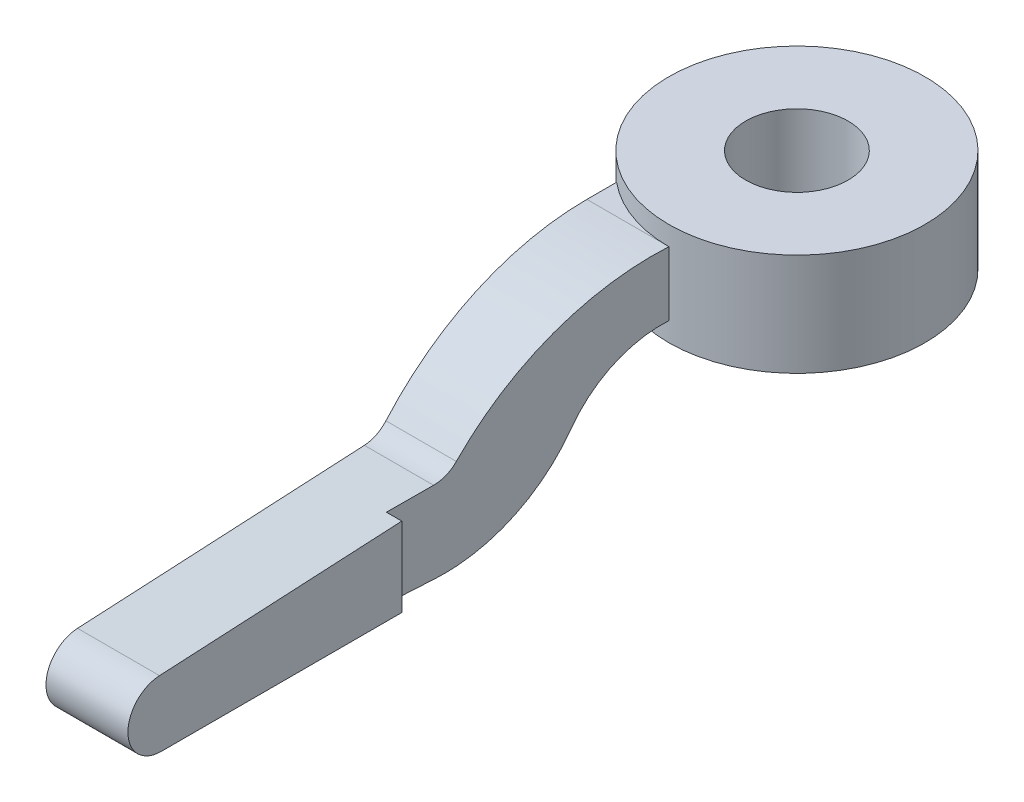
SolidWorks part; units mm, degrees
ref_plane "Front Plane" through (0, 0, 0) normal (0, 0, 1) x (1, 0, 0)
ref_plane "Top Plane" through (0, 0, 0) normal (0, 1, 0) x (1, 0, 0)
ref_plane "Right Plane" through (0, 0, 0) normal (1, 0, 0) x (0, 0, -1)
sketch "Sketch1" plane through (0, 0, 0) normal (0, 1, 0) x (1, 0, 0)
  circle A0 centre (0, 0) radius 1
  circle A1 centre (0, 0) radius 2.5
  dimension "D1" = 2
  dimension "D2" = 1.5
extrude "Boss-Extrude1" add sketch "Sketch1" along normal blind 2
ref_plane "Plane1" through (0, 0, 2.5) normal (0, 0, 1) x (1, 0, 0)
sketch "Sketch3" plane through (0, 0, 2.5) normal (0, 0, 1) x (1, 0, 0)
  line L0 (-0.8, 0) -> (0.8, 0) construction
  line L1 (-2.5, 0) -> (2.5, 0) construction
  line L2 (0.8, 0) -> (0.8, 2) construction
  line L3 (0.8, 2) -> (-0.8, 2) construction
  line L4 (-0.8, 2) -> (-0.8, 0) construction
  line L5 (0, 2) -> (0, 0) construction
  dimension "D1" = 2
  dimension "D2" = 1.6
ref_plane "Plane2" through (-0.8, 0, 0) normal (-1, 0, 0) x (0, -1, 0)
sketch "Sketch7" plane through (-0.8, 0, 0) normal (-1, 0, 0) x (0, -1, 0)
  line L0 (-1, 2.5) -> (-1, 3.7493) construction
  line L1 (-2, 2.5) -> (0, 2.5) construction
  line L3 (-0.3163, 2.5) -> (0.7605, 2.5) construction
  line L4 (1.954, 6.8096) -> (1.954, 12.4096)
  line L5 (0.6549, 12.4436) -> (0.3614, 6.8436)
  line L7 (-1.625, 2.5) -> (-1.625, 1.75)
  line L8 (-1.625, 1.75) -> (-0.375, 1.75)
  line L9 (-0.375, 1.75) -> (-0.375, 2.5)
  arc A0 (-0.375, 2.5) -> (0.5978, 4.3) centre (1.7767, 2.5) cw
  arc A1 (0.5978, 4.3) -> (1.954, 6.8096) centre (-1.046, 6.8096) ccw
  arc A2 (1.954, 12.4096) -> (0.6549, 12.4436) centre (1.304, 12.4096) ccw
  arc A3 (0.3614, 6.8436) -> (0.157, 6.4232) centre (-0.2378, 6.875) cw
  arc A4 (0.157, 6.4232) -> (-1.625, 2.5) centre (3.5845, 2.5) ccw
  point P18 (1.321, 13.0594)
  dimension "D4" = 0.9728
  dimension "D6" = 5.6
  dimension "D7" = 3
  dimension "D8" = 0.6
  dimension "D10" = 0.65
  dimension "D1" = 1.25
  dimension "D2" = 5.6
  dimension "D3" = 1.8
  dimension "D5" = 3
  dimension "D9" = 1.25
  dimension "D11" = 0.75
  dimension "D12" = 13.0594
extrude "Boss-Extrude2" add sketch "Sketch7" along normal mid plane 1.6
sketch "Sketch9" plane through (0, -1.954, 0) normal (0, -1, 0) x (1, 0, 0)
  line L0 (0, 2.5) -> (-0.3, 7.7137)
  line L1 (-0.3, 7.7137) -> (0, 7.7137)
  line L2 (0, 6.8096) -> (0, 12.4096) construction
  line L3 (0, 7.7137) -> (0, 2.5)
  dimension "D1" = 0.3
extrude "Cut-Extrude1" cut sketch "Sketch9" against normal through all
